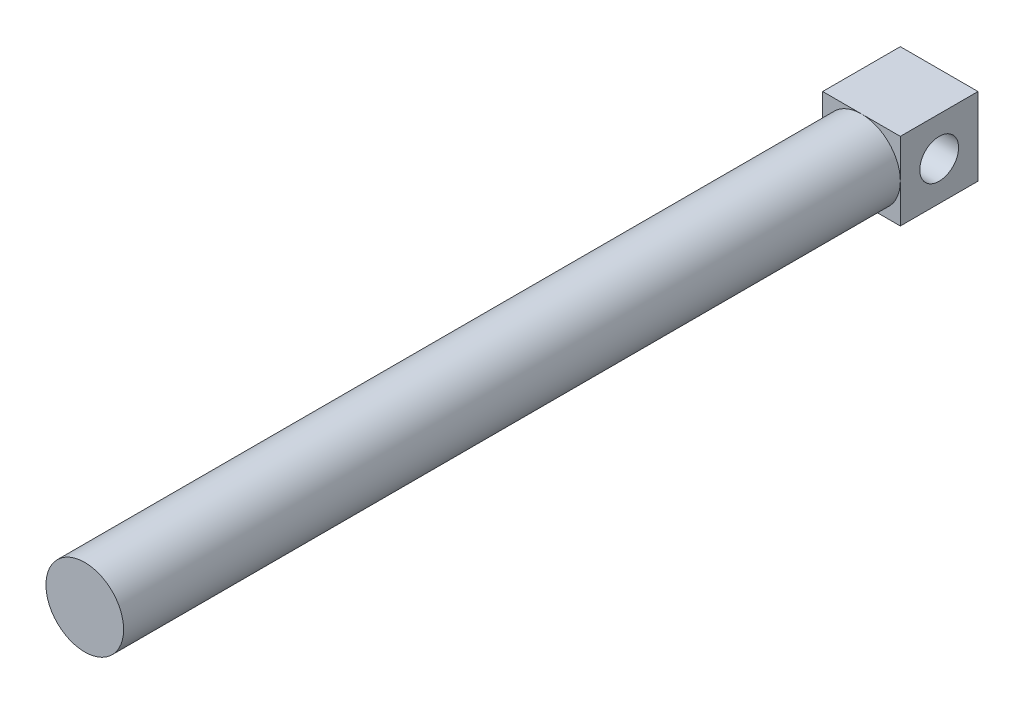
SolidWorks part; units mm, degrees
ref_plane "前视基准面" through (0, 0, 0) normal (0, 0, 1) x (1, 0, 0)
ref_plane "上视基准面" through (0, 0, 0) normal (0, 1, 0) x (1, 0, 0)
ref_plane "右视基准面" through (0, 0, 0) normal (1, 0, 0) x (0, 0, -1)
other "Configuration Table"
sketch "草图1" plane through (0, 0, 0) normal (0, 0, 1) x (1, 0, 0)
  circle A0 centre (0, 0) radius 5
  dimension "D1" = 10
extrude "凸台-拉伸1" add sketch "草图1" along normal blind 100
sketch "草图2" plane through (0, 0, 0) normal (0, 0, -1) x (-1, 0, 0)
  line L1 (-5, -5) -> (5, -5)
  line L2 (-5, -5) -> (-5, 5)
  line L3 (-5, 5) -> (5, 5)
  line L4 (5, -5) -> (5, 5)
  line L5 (-5, -5) -> (5, 5) construction
  line L6 (-5, 5) -> (5, -5) construction
  point P0 (0, 0)
  dimension "D1" = 10
  dimension "D2" = 10
extrude "凸台-拉伸2" add sketch "草图2" along normal blind 10
sketch "草图3" plane through (5, 0, 0) normal (1, 0, 0) x (0, 0, -1)
  line L0 (0, 5) -> (10, -5) construction
  line L1 (0, -5) -> (10, 5) construction
  line L5 (0, 5) -> (0, 0)
  line L6 (0, 0) -> (0, -5)
  line L7 (0, -5) -> (10, -5)
  line L8 (10, -5) -> (10, 5)
  line L9 (10, 5) -> (0, 5)
  line L10 (0, 5) -> (0, 0)
  line L11 (0, 0) -> (0, -5)
  line L12 (0, -5) -> (10, -5)
  line L13 (10, -5) -> (10, 5)
  line L14 (10, 5) -> (0, 5)
  circle A0 centre (5, 0) radius 2.5
  dimension "D2" = 5
  dimension "D1" = 0
extrude "切除-拉伸1" cut sketch "草图3" against normal through all contours A0
